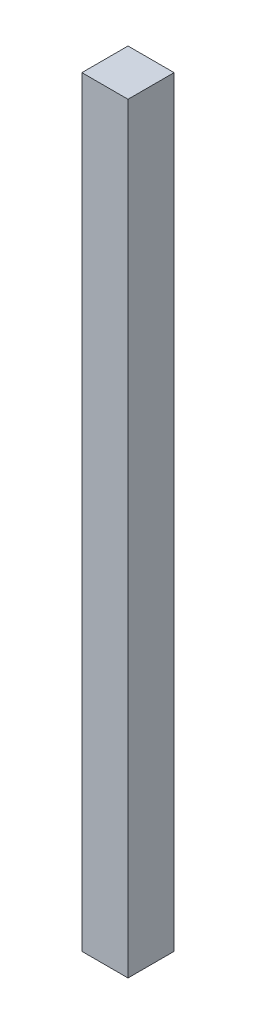
SolidWorks part; units mm, degrees
ref_plane "Front Plane" through (0, 0, 0) normal (0, 0, 1) x (1, 0, 0)
ref_plane "Top Plane" through (0, 0, 0) normal (0, 1, 0) x (1, 0, 0)
ref_plane "Right Plane" through (0, 0, 0) normal (1, 0, 0) x (0, 0, -1)
sketch "Sketch1" plane through (0, 0, 0) normal (0, 1, 0) x (1, 0, 0)
  line L1 (0, 0) -> (20, 0)
  line L2 (0, 0) -> (0, -20)
  line L3 (0, -20) -> (20, -20)
  line L4 (20, 0) -> (20, -20)
extrude "Boss-Extrude1" add sketch "Sketch1" along normal up to surface (330.0464 mm away)
